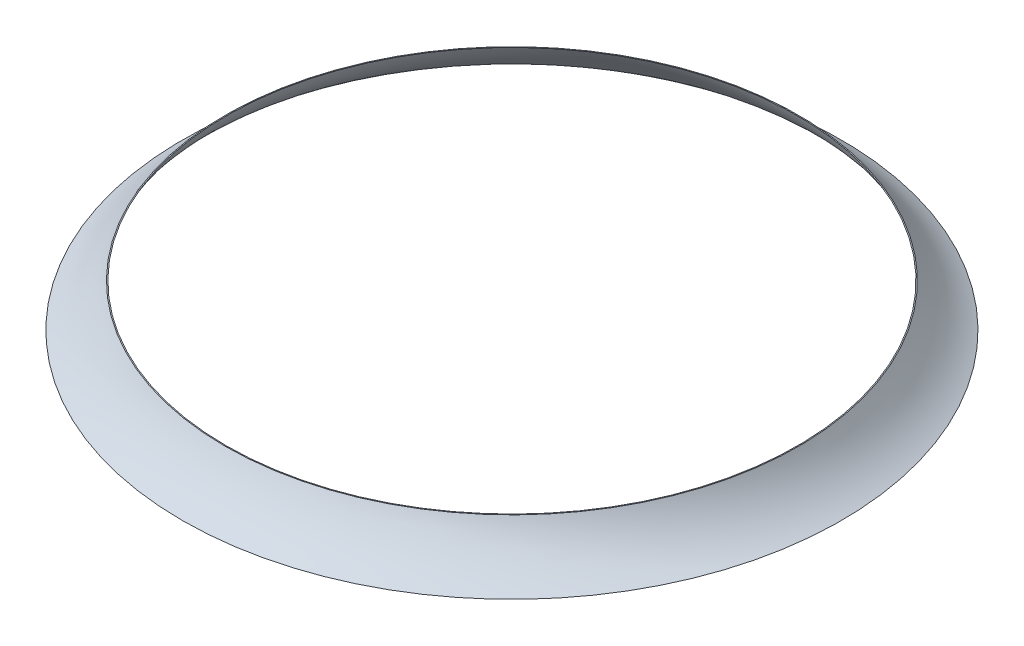
SolidWorks part; units mm, degrees
ref_plane "Front Plane" through (0, 0, 0) normal (0, 0, 1) x (1, 0, 0)
ref_plane "Top Plane" through (0, 0, 0) normal (0, 1, 0) x (1, 0, 0)
ref_plane "Right Plane" through (0, 0, 0) normal (1, 0, 0) x (0, 0, -1)
sketch "Sketch1" plane through (0, 0, 0) normal (1, 0, 0) x (0, 0, -1)
  line L0 (2016.3632, 1309.4766) -> (2013.5697, 1309.4766)
  line L1 (1213.3632, 1309.4766) -> (1213.3632, 1189.4766)
  line L2 (2136.3632, 1189.4766) -> (2130.8846, 1189.4766)
  arc A0 (2016.3632, 1309.4766) -> (2136.3632, 1189.4766) centre (2257.071, 1430.1844) ccw
  arc A1 (2013.5697, 1309.4766) -> (2130.8846, 1189.4766) centre (2257.071, 1430.1844) ccw
revolve "Revolve1" add sketch "Sketch1" angle 360 about L1
